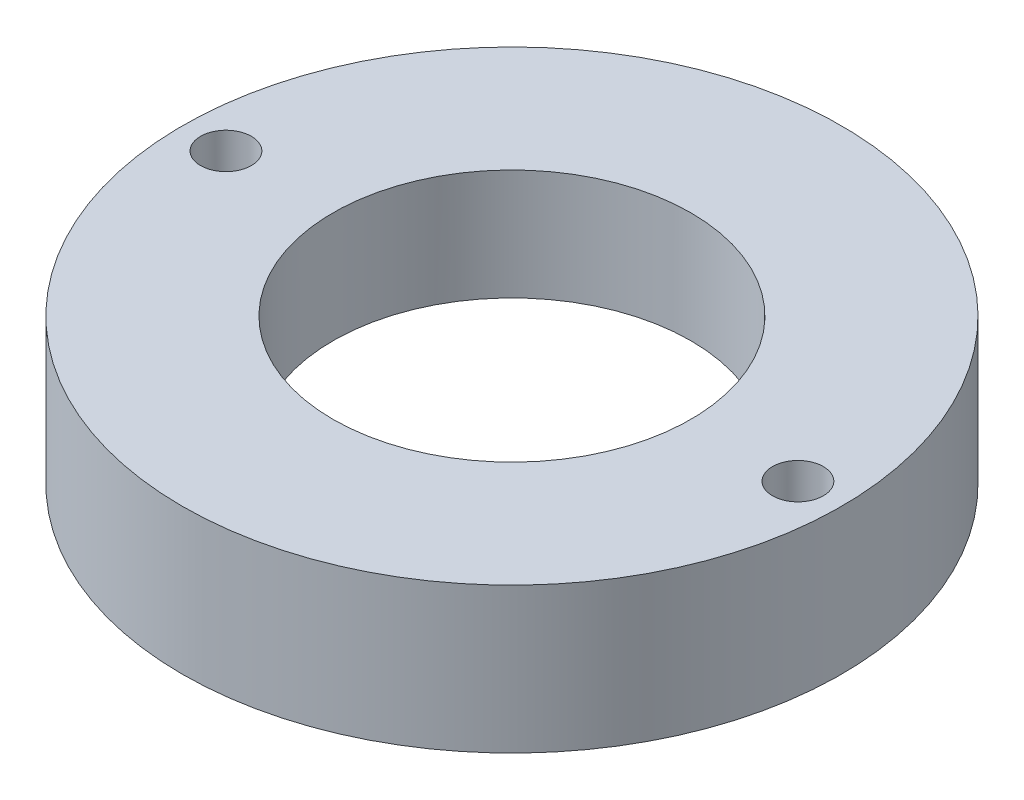
SolidWorks part; units mm, degrees
ref_plane "Front Plane" through (0, 0, 0) normal (0, 0, 1) x (1, 0, 0)
ref_plane "Top Plane" through (0, 0, 0) normal (0, 1, 0) x (1, 0, 0)
ref_plane "Right Plane" through (0, 0, 0) normal (1, 0, 0) x (0, 0, -1)
sketch "Sketch2" plane through (0, 0, 0) normal (0, 1, 0) x (1, 0, 0)
  circle A0 centre (0, 0) radius 28.55
  dimension "D1" = 57.1
extrude "Boss-Extrude1" add sketch "Sketch2" along normal blind 12.6 contours A0
sketch "Sketch3" plane through (0, 0, 0) normal (0, -1, 0) x (1, 0, 0)
  circle A0 centre (0, 0) radius 21
  dimension "D1" = 42
extrude "Cut-Extrude1" cut sketch "Sketch3" against normal blind 3
sketch "Sketch4" plane through (0, 3, 0) normal (0, -1, 0) x (1, 0, 0)
  circle A0 centre (0, 0) radius 15.5
  dimension "D1" = 31
extrude "Cut-Extrude2" cut sketch "Sketch4" against normal blind 24
sketch "Sketch5" plane through (0, 0, 0) normal (0, -1, 0) x (-1, 0, 0)
  line L0 (-21, 0) -> (-28.55, 0) construction
  circle A0 centre (0, 0) radius 21 construction
  circle A1 centre (0, 0) radius 28.55 construction
  circle A2 centre (-24.775, 0) radius 2.2
  dimension "D1" = 4.4
extrude "Cut-Extrude3" cut sketch "Sketch5" against normal blind 24
mirror "Mirror1" about plane through (0, 0, 0) normal (1, 0, 0) of "Cut-Extrude3"
